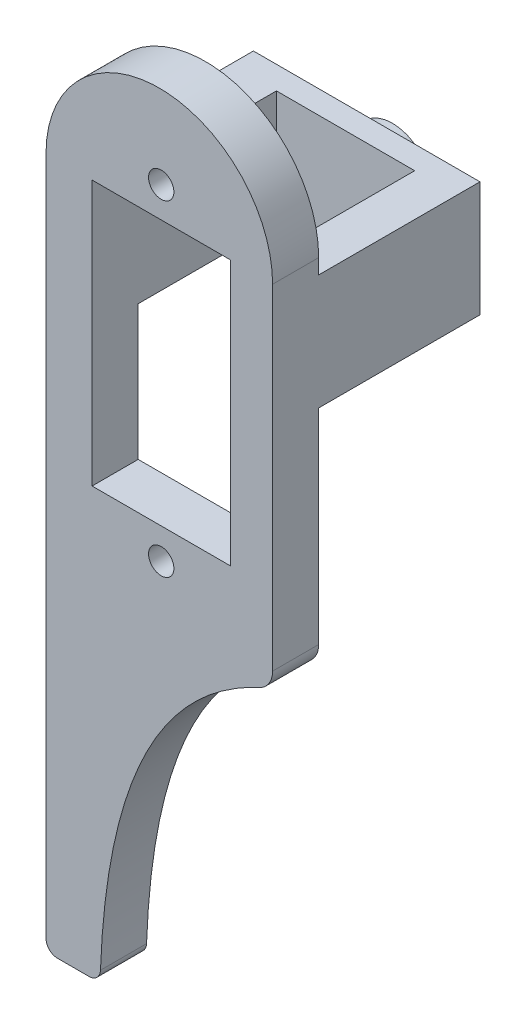
SolidWorks part; units mm, degrees
ref_plane "Front Plane" through (0, 0, 0) normal (0, 0, 1) x (1, 0, 0)
ref_plane "Top Plane" through (0, 0, 0) normal (0, 1, 0) x (1, 0, 0)
ref_plane "Right Plane" through (0, 0, 0) normal (1, 0, 0) x (0, 0, -1)
sketch "Sketch1" plane through (0, 0, 0) normal (0, 0, 1) x (1, 0, 0)
  line L0 (10.2196, 1.4347) -> (10.2196, -58.5653)
  line L4 (10.2196, -58.5653) -> (14.9213, -58.5653)
  line L5 (14.9213, -58.5653) -> (14.9213, -58.3072)
  line L6 (29.8859, -28.97) -> (29.8859, 1.4347)
  arc A1 (10.2196, 1.4347) -> (29.8859, 1.4347) centre (20.0527, 1.4347) cw
  spline S0 degree 2 poles (29.8859, -28.97) (15.6039, -34.5286) (14.9213, -58.3072) knots 0 0 0 1 1 1
  dimension "D2" = 9.8332
  dimension "D1" = 60
extrude "Boss-Extrude1" add sketch "Sketch1" along normal blind 4
sketch "Sketch2" plane through (0, 0, 4) normal (0, 0, 1) x (1, 0, 0)
  line L0 (10.2196, 1.4347) -> (14.2196, 1.4347) construction
  line L1 (14.2196, 1.4347) -> (26.2196, 1.4347)
  line L2 (14.2196, 1.4347) -> (14.2196, -21.5653)
  line L3 (14.2196, -21.5653) -> (26.2196, -21.5653)
  line L4 (26.2196, 1.4347) -> (26.2196, -21.5653)
  line L5 (10.2196, 1.4347) -> (10.2196, -58.5653) construction
  line L8 (20.2196, 4.0847) -> (20.2196, 1.4347) construction
  line L9 (20.2196, -21.5653) -> (20.2196, -24.2153) construction
  circle A0 centre (20.2196, 4.0847) radius 1.1
  circle A1 centre (20.2196, -24.2153) radius 1.1
  dimension "D4" = 2.2
  dimension "D1" = 23
  dimension "D2" = 12
  dimension "D3" = 4
  dimension "D5" = 2.65
  dimension "D6" = 2.65
extrude "Cut-Extrude1" cut sketch "Sketch2" against normal up to next
fillet "Fillet1" radius 2 1 edges at (29.8859, -28.97, 2)
fillet "Fillet2" radius 1 1 edges at (14.9213, -58.5653, 2)
fillet "Fillet3" radius 1 1 edges at (10.2196, -58.5653, 2)
sketch "Sketch3" plane through (0, 0, 0) normal (0, 0, -1) x (-1, 0, 0)
  line L0 (-29.8859, -27.6468) -> (-29.8859, 1.4347) construction
  line L1 (-29.8859, 0.1347) -> (-26.2196, 0.1347)
  line L2 (-29.8859, 0.1347) -> (-29.8859, -9.8653)
  line L3 (-29.8859, -9.8653) -> (-26.2196, -9.8653)
  line L4 (-26.2196, 0.1347) -> (-26.2196, -9.8653)
  line L5 (-26.2196, -21.5653) -> (-26.2196, 1.4347) construction
  line L6 (-14.2196, 1.4347) -> (-14.2196, -21.5653) construction
  line L7 (-14.2196, 0.1347) -> (-10.2196, 0.1347)
  line L8 (-14.2196, 0.1347) -> (-14.2196, -9.8653)
  line L9 (-14.2196, -9.8653) -> (-10.2196, -9.8653)
  line L10 (-10.2196, 0.1347) -> (-10.2196, -9.8653)
  line L11 (-10.2196, 1.4347) -> (-10.2196, -57.5653) construction
  line L12 (-26.2196, 1.4347) -> (-14.2196, 1.4347) construction
  dimension "D1" = 10
  dimension "D2" = 1.3
  dimension "D3" = 1.3
extrude "Boss-Extrude2" add sketch "Sketch3" along normal blind 12
sketch "Sketch4" plane through (0, 0, -12) normal (0, 0, -1) x (-1, 0, 0)
  line L1 (-29.8859, 0.1347) -> (-10.2196, 0.1347)
  line L2 (-29.8859, 0.1347) -> (-29.8859, -9.8653)
  line L3 (-29.8859, -9.8653) -> (-10.2196, -9.8653)
  line L4 (-10.2196, 0.1347) -> (-10.2196, -9.8653)
extrude "Boss-Extrude3" add sketch "Sketch4" along normal blind 2
sketch "Sketch5" plane through (0, 0, -14) normal (0, 0, -1) x (-1, 0, 0)
  line L0 (-29.8859, 0.1347) -> (-29.8859, -9.8653) construction
  line L2 (-10.2196, 0.1347) -> (-29.8859, 0.1347) construction
  circle A0 centre (-20.2859, -4.6653) radius 3.4
  dimension "D1" = 6.8
  dimension "D2" = 9.6
  dimension "D3" = 4.8
extrude "Boss-Extrude4" add sketch "Sketch5" along normal blind 2
